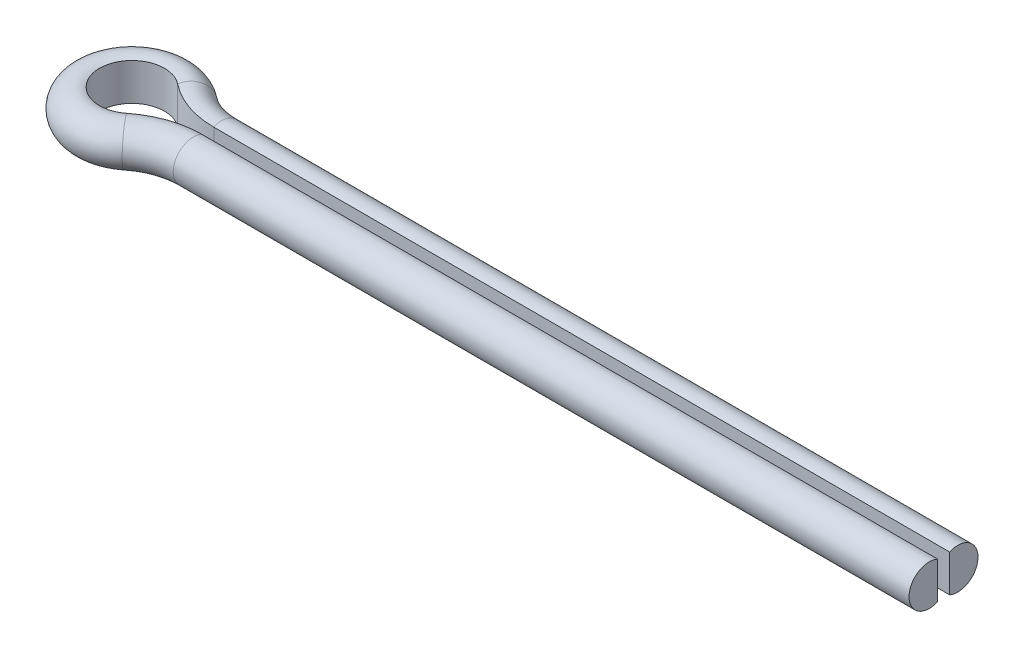
SolidWorks part; units mm, degrees
ref_plane "Front Plane" through (0, 0, 0) normal (0, 0, 1) x (1, 0, 0)
ref_plane "Top Plane" through (0, 0, 0) normal (0, 1, 0) x (1, 0, 0)
ref_plane "Right Plane" through (0, 0, 0) normal (1, 0, 0) x (0, 0, -1)
sketch "Sketch1" plane through (0, 0, 0) normal (0, 1, 0) x (1, 0, 0)
  line L0 (-40.9373, 0) -> (47.1686, 0) construction
  line L1 (0, 27.6465) -> (0, -24.5703) construction
  line L2 (9.324, 1.75) -> (100, 1.75)
  line L3 (9.324, -1.75) -> (100, -1.75)
  arc A0 (3.108, 3.9167) -> (3.108, -3.9167) centre (0, 0) ccw
  arc A1 (3.108, -3.9167) -> (9.324, -1.75) centre (9.324, -11.75) cw
  arc A2 (9.324, 1.75) -> (3.108, 3.9167) centre (9.324, 11.75) cw
  point P11 (0, 0)
  point P13 (4.6837, -1.75)
  point P16 (4.6837, 1.75)
  dimension "D1" = 10
  dimension "D3" = 10
  dimension "D2" = 3.5
  dimension "D4" = 100
ref_plane "Plane1" through (100, 0, -1.75) normal (1, 0, 0) x (0, 0, -1)
sketch "Sketch2" plane through (100, 0, -1.75) normal (1, 0, 0) x (0, 0, -1)
  line L0 (-1, -2.2913) -> (-1, 2.2913)
  arc A0 (-1, -2.2913) -> (-1, 2.2913) centre (0, 0) ccw
  dimension "D1" = 5
  dimension "D2" = 1
sweep "Sweep1" add profiles "Sketch2" path "Sketch1"
